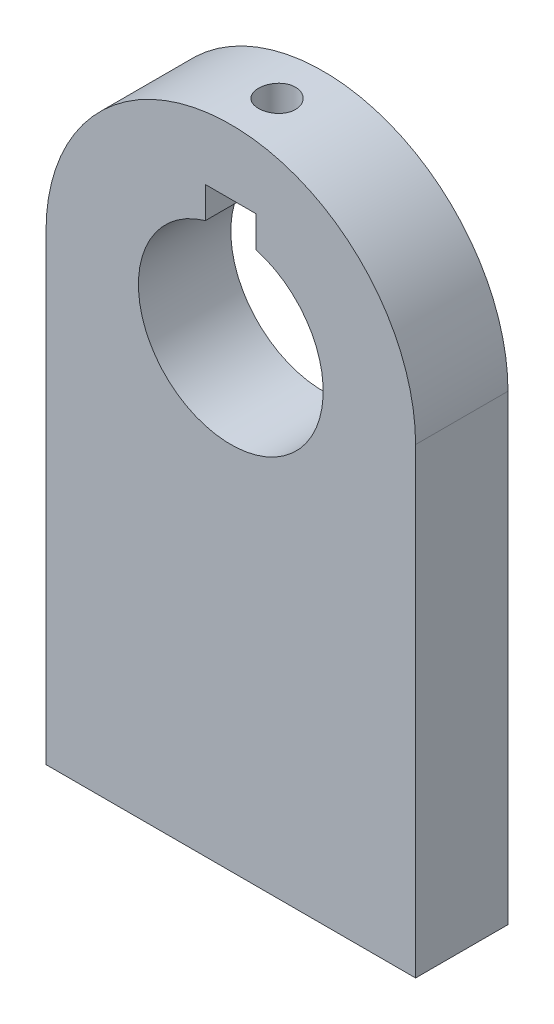
SolidWorks part; units mm, degrees
ref_plane "Front Plane" through (0, 0, 0) normal (0, 0, 1) x (1, 0, 0)
ref_plane "Top Plane" through (0, 0, 0) normal (0, 1, 0) x (1, 0, 0)
ref_plane "Right Plane" through (0, 0, 0) normal (1, 0, 0) x (0, 0, -1)
sketch "Sketch1" plane through (0, 0, 0) normal (0, 0, 1) x (1, 0, 0)
  line L0 (0, 0) -> (-20, 0) construction
  line L1 (0, 0) -> (20, 0) construction
  line L2 (-20, 0) -> (-20, -50)
  line L3 (-20, -50) -> (20, -50)
  line L4 (20, -50) -> (20, 0)
  circle A0 centre (0, 0) radius 10
  arc A1 (-20, 0) -> (20, 0) centre (0, 0) cw
  dimension "D1" = 20
  dimension "D2" = 20
  dimension "D3" = 20
  dimension "D4" = 50
extrude "Boss-Extrude1" add sketch "Sketch1" along normal blind 10
sketch "Sketch3" plane through (0, 0, 10) normal (0, 0, 1) x (1, 0, 0)
  line L0 (0, 0) -> (0, 11.25) construction
  line L2 (-2.75, 13) -> (2.75, 13)
  line L3 (-2.75, 13) -> (-2.75, 9.5)
  line L4 (-2.75, 9.5) -> (2.75, 9.5)
  line L5 (2.75, 13) -> (2.75, 9.5)
  line L6 (-2.75, 13) -> (2.75, 9.5) construction
  line L7 (-2.75, 9.5) -> (2.75, 13) construction
  dimension "D1" = 11.25
  dimension "D2" = 3.5
  dimension "D3" = 5.5
extrude "Cut-Extrude2" cut sketch "Sketch3" against normal blind 11
sketch "Sketch4" plane through (0, 13, 0) normal (0, -1, 0) x (1, 0, 0)
  line L1 (0, 0) -> (0, 5) construction
  line L2 (0, 10) -> (0, 0) construction
  circle A0 centre (0, 5) radius 2
  dimension "D2" = 4
  dimension "D1" = 5
extrude "Cut-Extrude3" cut sketch "Sketch4" against normal blind 7
